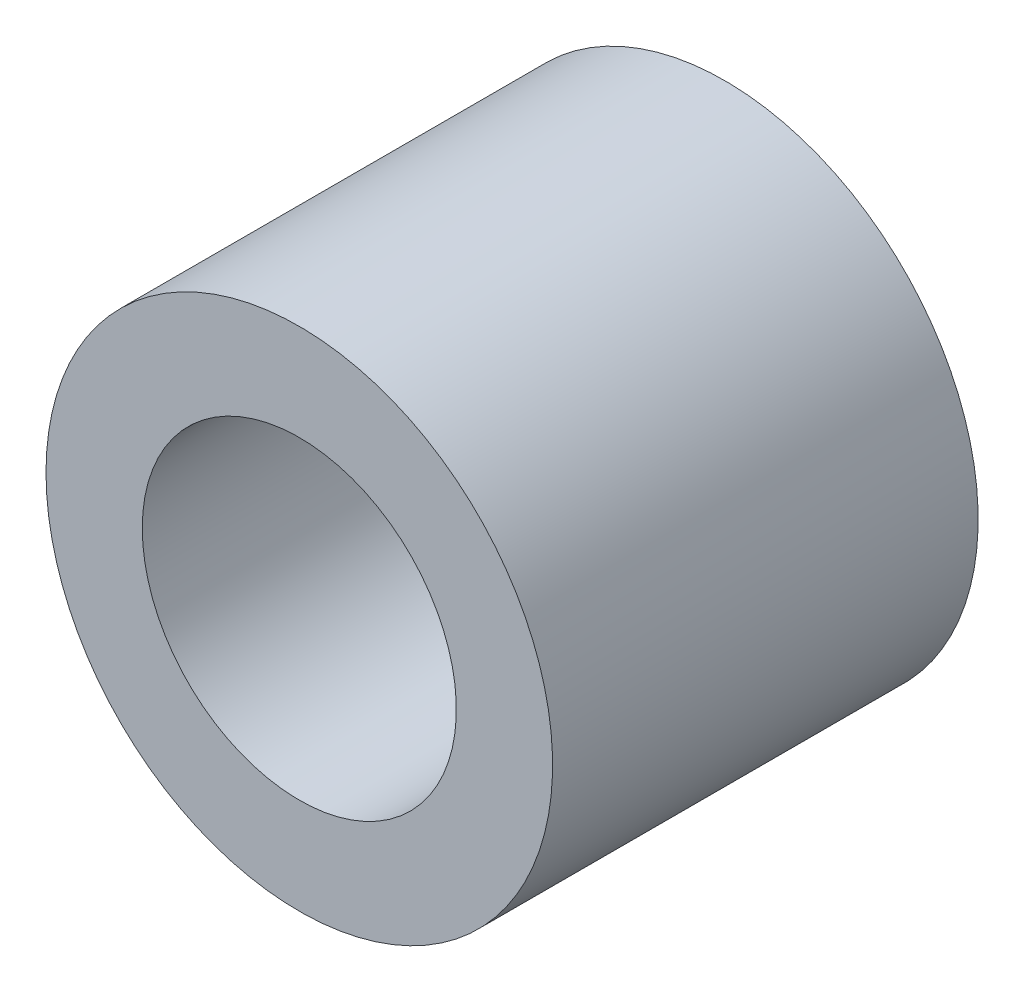
SolidWorks part; units mm, degrees
ref_plane "Plano frontal" through (0, 0, 0) normal (0, 0, 1) x (1, 0, 0)
ref_plane "Plano superior" through (0, 0, 0) normal (0, 1, 0) x (1, 0, 0)
ref_plane "Plano direito" through (0, 0, 0) normal (1, 0, 0) x (0, 0, -1)
sketch "Esboço1" plane through (0, 0, 3.7365) normal (0, 0, -1) x (-1, 0, 0)
  circle A0 centre (-11.7233, -79.9392) radius 1.55
  circle A1 centre (-11.7233, -79.9392) radius 2.5
  dimension "D1" = 3.1
  dimension "D2" = 5
extrude "Ressalto-extrusão1" add sketch "Esboço1" along normal up to surface (4.2 mm away)
